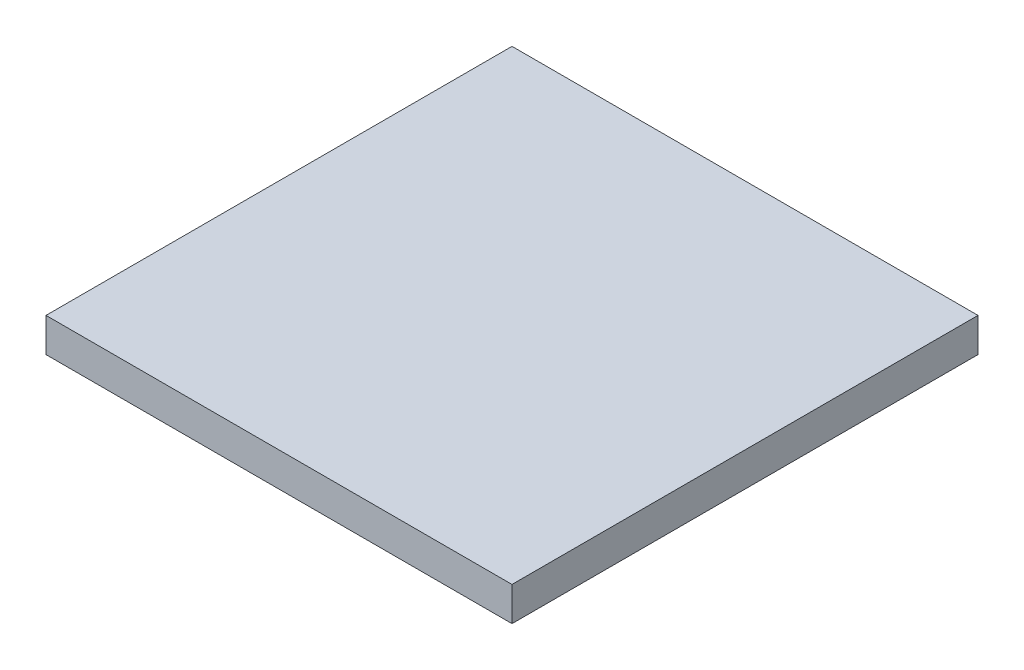
SolidWorks part; units mm, degrees
ref_plane "Front Plane" through (0, 0, 0) normal (0, 0, 1) x (1, 0, 0)
ref_plane "Top Plane" through (0, 0, 0) normal (0, 1, 0) x (1, 0, 0)
ref_plane "Right Plane" through (0, 0, 0) normal (1, 0, 0) x (0, 0, -1)
sketch "Sketch1" plane through (0, 0, 0) normal (0, 1, 0) x (1, 0, 0)
  line L1 (171.45, -171.45) -> (-171.45, -171.45)
  line L2 (171.45, -171.45) -> (171.45, 171.45)
  line L3 (171.45, 171.45) -> (-171.45, 171.45)
  line L4 (-171.45, -171.45) -> (-171.45, 171.45)
  line L5 (171.45, -171.45) -> (-171.45, 171.45) construction
  line L6 (171.45, 171.45) -> (-171.45, -171.45) construction
  point P0 (0, 0)
  dimension "D1" = 342.9
extrude "Boss-Extrude1" add sketch "Sketch1" against normal blind 25
